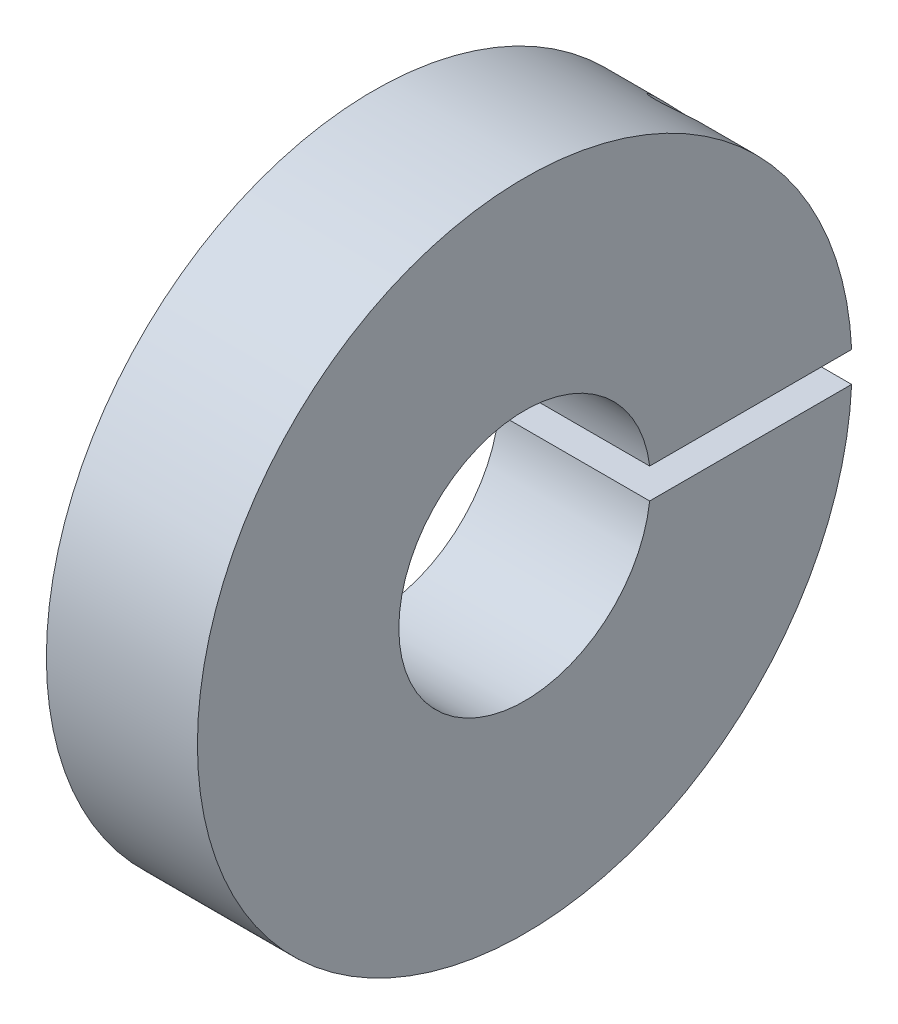
SolidWorks part; units mm, degrees
ref_plane "Front Plane" through (0, 0, 0) normal (0, 0, 1) x (1, 0, 0)
ref_plane "Top Plane" through (0, 0, 0) normal (0, 1, 0) x (1, 0, 0)
ref_plane "Right Plane" through (0, 0, 0) normal (1, 0, 0) x (0, 0, -1)
sketch "Sketch1" plane through (0, 0, 0) normal (1, 0, 0) x (0, 0, -1)
  circle A0 centre (0, 0) radius 3.175
  circle A1 centre (0, 0) radius 8.255
  dimension "D1" = 6.35
  dimension "D2" = 5.08
extrude "Boss-Extrude1" add sketch "Sketch1" along normal mid plane 3.81
sketch "Sketch3" plane through (0, 0, 0) normal (0, 1, 0) x (1, 0, 0)
  line L0 (-1.905, 0) -> (1.905, 0) construction
  line L1 (-1.905, 8.255) -> (-1.905, -8.255) construction
  line L2 (1.905, -8.255) -> (1.905, 8.255) construction
  line L4 (-1.905, 0) -> (1.905, 0)
  line L5 (-1.905, 0) -> (-1.905, 8.255)
  line L6 (-1.905, 8.255) -> (1.905, 8.255)
  line L7 (1.905, 0) -> (1.905, 8.255)
extrude "Cut-Extrude1" cut sketch "Sketch3" against normal mid plane 0.762
sketch "Sketch4" plane through (0, 0, 0) normal (0, 1, 0) x (1, 0, 0)
  line L0 (0, 0) -> (0, 8.2462) construction
  line L1 (-1.905, 8.2462) -> (1.905, 8.2462) construction
  circle A0 centre (0, 5.7062) radius 0.508
  dimension "D1" = 1.016
  dimension "D2" = 2.54
extrude "Cut-Extrude2" cut sketch "Sketch4" against normal through all both and the other way through all
